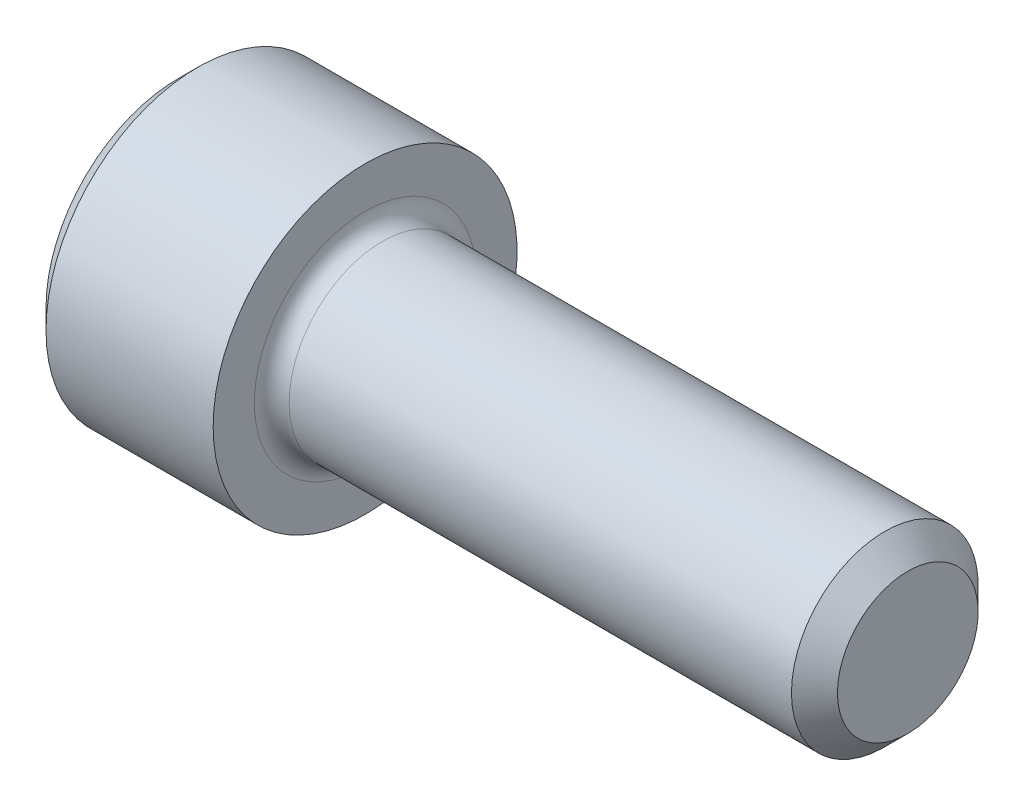
SolidWorks part; units mm, degrees
ref_plane "Plane1" through (0, 0, 0) normal (0, 0, 1) x (1, 0, 0)
ref_plane "Plane2" through (0, 0, 0) normal (0, 1, 0) x (1, 0, 0)
ref_plane "Plane3" through (0, 0, 0) normal (1, 0, 0) x (0, 0, -1)
sketch "BodySke" plane through (0, 0, 0) normal (0, 0, 1) x (1, 0, 0)
  line L0 (0, 0) -> (0, 1.5494)
  line L1 (0.2286, 1.778) -> (2.1844, 1.778)
  line L2 (2.1844, 1.778) -> (2.1844, 1.0922)
  line L3 (2.1844, 1.0922) -> (8.2652, 1.0922)
  line L4 (8.5344, 0.823) -> (8.5344, 0)
  line L5 (8.5344, 0) -> (0, 0)
  line L6 (-31.75, 0) -> (127, 0) construction
  line L7 (0, 1.5494) -> (0.2286, 1.778)
  line L8 (8.5344, 0.823) -> (8.2652, 1.0922)
  line L9 (0, -1.5494) -> (0.2286, -1.778) construction
  line L10 (8.5344, -0.823) -> (8.2652, -1.0922) construction
  line L11 (2.6391, 9.525) -> (2.6391, 3.175) construction
  line L12 (2.1844, 9.525) -> (2.1844, 3.175) construction
  line L13 (-29.5656, 9.525) -> (-29.5656, 3.175) construction
  dimension "Diameter" = 2.1844
  dimension "Head_ht" = 2.1844
  dimension "Length" = 6.35
  dimension "Body_ch_ang" = 45
  dimension "Head_dia" = 3.556
  dimension "Head_ch_ang" = 45
  dimension "Head_side_ht" = 1.9558
  dimension "Minor_dia" = 1.6459
  dimension "Advance" = 0.4547
  dimension "Thread_nom" = 6.35
  dimension "Thread_length" = 38.1
revolve "Base-Revolve" add sketch "BodySke"
cosmetic thread "ThreadCosmetic" [suppressed]
fillet "Fillet1" radius 0.2032 1 edges at (2.1844, 0, 1.0922)
sketch "Sketch2" plane through (0, 0, 0) normal (0, 0, 1) x (1, 0, 0)
  line L0 (0, 0.9906) -> (0.9652, 0.9906)
  line L1 (0.9652, 0.9906) -> (1.5371, 0)
  line L2 (-31.75, 0) -> (127, 0) construction
  line L3 (1.5371, 0) -> (0, 0)
  line L4 (0, 0) -> (0, 0.9906)
  line L5 (0, 1.5494) -> (0, -1.5494) construction
  line L6 (0, 0) -> (47.625, 0) construction
  line L7 (2.1844, -1.778) -> (2.1844, 1.778) construction
  dimension "D1" = 0.9906
  dimension "D2" = 60
  dimension "Wall_thickness" = 1.2192
revolve "Hex-PreBroach" cut sketch "Sketch2" angle 360 about L6
sketch "Sketch3" plane through (0, 0, 0) normal (-1, 0, 0) x (0, 0.5, 0.866)
  line L0 (0.5719, 0.9906) -> (-0.5719, 0.9906)
  line L1 (-0.5719, 0.9906) -> (-1.1438, 0)
  line L2 (0.5719, 0.9906) -> (1.1438, 0)
  line L3 (0.5719, -0.9906) -> (1.1438, 0)
  line L4 (0.5719, -0.9906) -> (-0.5719, -0.9906)
  line L5 (-0.5719, -0.9906) -> (-1.1438, 0)
  dimension "D1" = 0.9906
  dimension "D2" = 0.9906
  dimension "Hex_size" = 1.9812
extrude "Hex" cut sketch "Sketch3" against normal blind 0.9652
sketch "Sketch4" plane through (0, 0, 0) normal (-1, 0, 0) x (0, 0, 1)
  line L0 (0, 0) -> (1.2446, 0)
  line L1 (0, 0) -> (6.1484, 3.5498) construction
  line L2 (0, 0) -> (0.6223, 1.0779)
  line L3 (1.0085, 0.2596) -> (1.19, 0.3644)
  line L4 (0.7291, 0.7436) -> (0.9106, 0.8484)
  arc A0 (1.0085, 0.2596) -> (0.7291, 0.7436) centre (0, 0) ccw
  arc A1 (1.2446, 0) -> (1.19, 0.3644) centre (0, 0) ccw
  arc A2 (0.6223, 1.0779) -> (0.9106, 0.8484) centre (0, 0) cw
  dimension "D1" = 30
  dimension "Spline_n_dim" = 2.0828
  dimension "Spline_m_dim" = 2.4892
  dimension "D2" = 60
  dimension "D3" = 0.2794
  dimension "Spline_p_dim" = 0.5588
extrude "Spline" [suppressed] cut sketch "Sketch4" against normal blind 0.9652
pattern_circular "CirPattern1" [suppressed] count 6 every 60
sketch "Sketch5" plane through (0, 0, 0) normal (0, 0, 1) x (1, 0, 0)
  line L0 (-31.75, 0) -> (127, 0) construction
  line L2 (0, 1.5494) -> (0, -1.5494) construction
  circle A0 centre (0.254, 0) radius 0.0127
  dimension "Drilled_hole_dia" = 0.0254
  dimension "Drilled_hole_loc" = 0.254
extrude "Hole" [suppressed] cut sketch "Sketch5" against normal through all and the other way through all
pattern_circular "Drilled-4" [suppressed] count 2 every 60
pattern_circular "Drilled-6" [suppressed] count 3 every 60
sketch "ThdSchSke" plane through (0, 0, 0) normal (0, 0, 1) x (1, 0, 0)
  line L0 (2.6391, -0.823) -> (2.4505, -1.0922)
  line L1 (2.6391, -0.823) -> (2.8276, -1.0922)
  line L2 (2.8276, -1.0922) -> (2.8276, -1.3653)
  line L3 (-3.175, 0) -> (5.1513, 0) construction
  line L5 (2.8276, -1.3653) -> (2.4505, -1.3653)
  line L6 (2.4505, -1.3653) -> (2.4505, -1.0922)
  line L7 (0, 1.5494) -> (0, -1.5494) construction
  dimension "Thread_minor" = 1.6459
  dimension "Diameter" = 2.1844
  dimension "Start" = 2.6391
  dimension "SideAngle" = 55
  dimension "VeeAngle" = 70
  dimension "Overcut" = 2.7305
revolve "ThreadSchematic" [suppressed] cut sketch "ThdSchSke" angle 360 about L3
pattern_linear "ThdSchPat" [suppressed]
equation "\"D2@Sketch3\" = \"Hex_size@Sketch3\" / 2"
equation "\"D1@Sketch3\" = \"Hex_size@Sketch3\" / 2"
equation "\"D1@Sketch2\" = \"Hex_size@Sketch3\" / 2"
equation "\"D3@Sketch4\" = \"Spline_p_dim@Sketch4\" / 2"
equation "\"Thread_minor@ThreadCosmetic\"  =  \"Minor_dia@BodySke\""
equation "\"D2@CirPattern1\" = 360 / \"Num_teeth@CirPattern1\""
equation "\"Wall_thickness@Sketch2\" = \"Head_ht@BodySke\" - \"Key_eng@Hex\""
equation "\"Thread_length@ThreadCosmetic\" = ((sgn( (\"Length@BodySke\" - \"Advance@BodySke\" ) - \"Thread_nom@BodySke\" )-1)*( (\"Length@BodySke\" - \"Advance@BodySke\" ) - \"Thread_nom@BodySke\" ))/-2+ \"Thread_nom@BodySke\""
equation "\"Thread_minor@ThdSchSke\" = \"Minor_dia@BodySke\""
equation "\"Diameter@ThdSchSke\" = \"Diameter@BodySke\""
equation "\"Overcut@ThdSchSke\" = \"Diameter@BodySke\" * 1.25"
equation "\"Start@ThdSchSke\" = \"Head_ht@BodySke\" + \"Length@BodySke\" - \"Thread_length@ThreadCosmetic\"  '---Non-countersunk---"
equation "\"Num_threads@ThdSchPat\" = int( \"Thread_length@ThreadCosmetic\" / \"Advance@BodySke\" + 0.999 )  + 1"
equation "\"Advance@ThdSchPat\" = \"Thread_length@ThreadCosmetic\" /  (\"Num_threads@ThdSchPat\" - 1) 'relax it"
equation "\"Num_threads@ThdSchPat\" = \"Num_threads@ThdSchPat\" - sgn( \"Num_threads@ThdSchPat\" - 1) '---chamfered tips only---"
